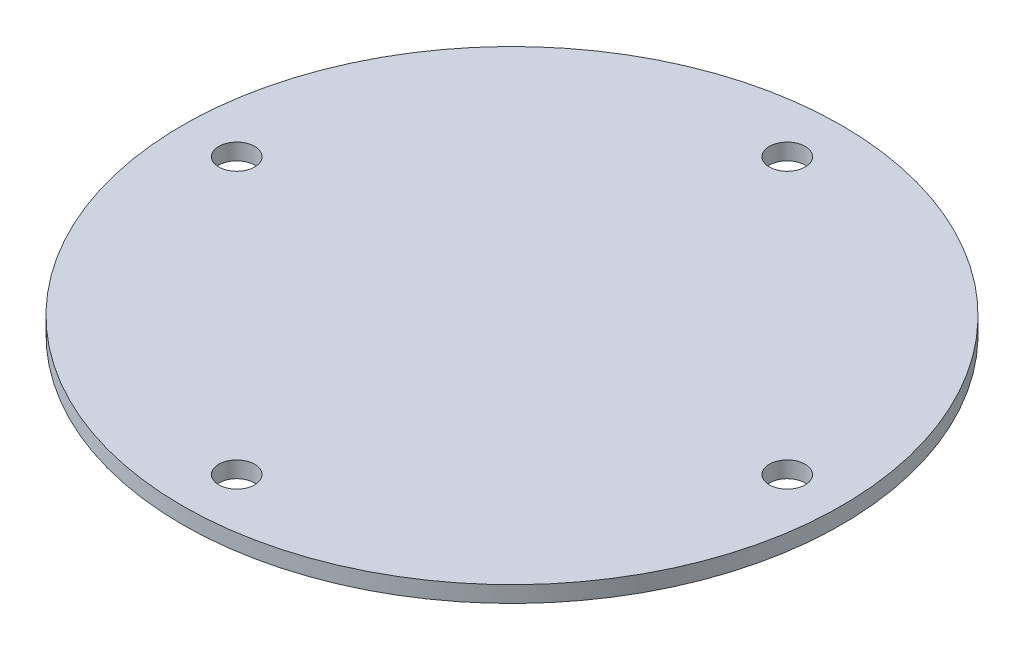
SolidWorks part; units mm, degrees
ref_plane "Front Plane" through (0, 0, 0) normal (0, 0, 1) x (1, 0, 0)
ref_plane "Top Plane" through (0, 0, 0) normal (0, 1, 0) x (1, 0, 0)
ref_plane "Right Plane" through (0, 0, 0) normal (1, 0, 0) x (0, 0, -1)
sketch "Sketch1" plane through (0, 0, 0) normal (0, 1, 0) x (1, 0, 0)
  circle A0 centre (0, 0) radius 60.7
  dimension "Diameter" = 121.4
extrude "Boss-Extrude1" add sketch "Sketch1" along normal mid plane 3
hole_wizard "M6 Clearance Hole1" positions "Sketch8" profile "Sketch9" hole size "M6" standard "ANSI Metric" end condition up to next
sketch "Sketch8" plane through (0, 1.5, 0) normal (0, 1, 0) x (1, 0, 0)
  line L0 (0, 0) -> (50.7, 0) construction
  point P0 (50.7, 0)
  dimension "ThreadedHoleDistance" = 50.7
sketch "Sketch9" plane through (50.7, 1.5, 0) normal (1, 0, 0) x (0, 0, 1)
  line L0 (0, 0) -> (0, 3)
  line L1 (0, 3) -> (3.3, 3)
  line L2 (3.3, 3) -> (3.3, 0)
  line L5 (3.3, 0) -> (0, 0)
  line L11 (0, -6.35) -> (0, 107.95) construction
  dimension "Thru Hole Dia." = 6.6
  dimension "Thru Hole Depth" = 3
pattern_circular "CirPattern2" count 4 over 360 about axis through (0, 0, 0) along (0, 1, 0) of "M6 Clearance Hole1"
sketch "Sketch5" [suppressed] plane through (0, 1.5, 0) normal (0, 1, 0) x (1, 0, 0)
  line L0 (0, 0) -> (65.4, 0) construction
  line L2 (0, 0) -> (39.1737, 39.1737) construction
  circle A0 centre (0, 0) radius 65.4 construction
  dimension "D1" = 45
  dimension " NoseShellHoleRadius" = 0
hole_wizard "M4 Clearance Hole1" [suppressed] positions "Sketch6" profile "Sketch7" hole size "M4" standard "ANSI Metric"
sketch "Sketch6" plane through (0, 1.5, 0) normal (0, 1, 0) x (1, 0, 0)
  point P0 (39.1737, 39.1737)
sketch "Sketch7" plane through (39.1737, 1.5, -39.1737) normal (1, 0, 0) x (0, 0, 1)
  line L0 (0, 0) -> (0, 3)
  line L1 (0, 3) -> (2.15, 3)
  line L2 (2.15, 3) -> (2.15, 0)
  line L5 (2.15, 0) -> (0, 0)
  line L11 (0, -6.35) -> (0, 107.95) construction
  dimension "Thru Hole Dia." = 4.3
  dimension "Thru Hole Depth" = 3
pattern_circular "CirPattern1" [suppressed] count 4 over 360
sketch "Sketch10" [suppressed] plane through (0, 1.5, 0) normal (0, 1, 0) x (1, 0, 0)
  circle A0 centre (0, 0) radius 7.5
  dimension "D1" = 15
extrude "Cut-Extrude1" [suppressed] cut sketch "Sketch10" against normal through all
sketch "Sketch11" [suppressed] plane through (0, -1.5, 0) normal (0, -1, 0) x (1, 0, 0)
  circle A0 centre (-14.75, -5) radius 2.25
  arc A1 (-16.7656, -6) -> (-16.7656, -4) centre (-14.75, -5) ccw construction
  circle A2 centre (-14.75, 5) radius 2.25
  circle A3 centre (34.75, -5) radius 2.25
  circle A4 centre (34.75, 5) radius 2.25
  arc A5 (-16.7656, 4) -> (-16.7656, 6) centre (-14.75, 5) ccw construction
  arc A6 (36.7656, 6) -> (36.7656, 4) centre (34.75, 5) ccw construction
  arc A7 (36.7656, -4) -> (36.7656, -6) centre (34.75, -5) ccw construction
extrude "Cut-Extrude2" [suppressed] cut sketch "Sketch11" against normal through all
sketch "Sketch12" [suppressed] plane through (0, 1.5, 0) normal (0, 1, 0) x (1, 0, 0)
  circle A0 centre (0, 0) radius 65.4 construction
  circle A1 centre (0, 0) radius 65.4
sketch "Sketch13" [suppressed] plane through (0, 1.5, 0) normal (0, 1, 0) x (1, 0, 0)
  line L0 (33.5571, -56.1345) -> (22.4418, -39.5077)
  line L1 (22.4418, -39.5077) -> (27.9287, -35.8397)
  line L2 (27.9287, -35.8397) -> (39.0439, -52.4665)
  line L3 (25.1853, -37.6737) -> (36.3468, -54.3698) construction
  line L4 (25.1853, -37.6737) -> (0, 0) construction
  line L5 (0, 0) -> (0, -55.4) construction
  line L6 (-7.3072, -48.0722) -> (-7.2822, -48.1318)
  line L7 (-7.3072, -48.0722) -> (-7.2822, -48.1318) construction
  line L8 (5.9654, -54.6476) -> (4.6633, -61.2016)
  line L9 (5.9654, -54.6476) -> (4.6633, -61.2016) construction
  line L10 (-13.8383, -61.9557) -> (-10.6131, -45.7223)
  line L11 (-13.8383, -61.9557) -> (-10.6131, -45.7223) construction
  line L12 (-10.6131, -45.7223) -> (-9.717, -41.2115)
  line L13 (-10.6131, -45.7223) -> (-9.717, -41.2115) construction
  line L14 (-9.717, -41.2115) -> (-8.0847, -32.9958)
  line L15 (-9.717, -41.2115) -> (-8.0847, -32.9958) construction
  line L16 (-8.0847, -32.9958) -> (-7.2796, -28.9433)
  line L17 (-8.0847, -32.9958) -> (-7.2796, -28.9433) construction
  line L18 (-7.2796, -28.9433) -> (-2.2975, -3.8666)
  line L19 (-7.2796, -28.9433) -> (-2.2975, -3.8666) construction
  line L20 (-2.2975, -3.8666) -> (0.645, -4.4512)
  line L21 (-2.2975, -3.8666) -> (0.645, -4.4512) construction
  line L22 (0.645, -4.4512) -> (-4.3371, -29.5279)
  line L23 (0.645, -4.4512) -> (-4.3371, -29.5279) construction
  line L24 (-4.3371, -29.5279) -> (-5.1422, -33.5804)
  line L25 (-4.3371, -29.5279) -> (-5.1422, -33.5804) construction
  line L26 (-5.1422, -33.5804) -> (-6.7745, -41.7961)
  line L27 (-5.1422, -33.5804) -> (-6.7745, -41.7961) construction
  line L28 (-6.7745, -41.7961) -> (-7.6706, -46.3069)
  line L29 (-6.7745, -41.7961) -> (-7.6706, -46.3069) construction
  circle A0 centre (0, 0) radius 65.4 construction
  circle A1 centre (0, 0) radius 65.4
  arc A2 (33.5571, -56.1345) -> (39.0439, -52.4665) centre (0, 0) ccw
  arc A3 (-7.2822, -48.1318) -> (0.9663, -48.6742) centre (0.0376, 0.1893) ccw
  arc A4 (-7.2822, -48.1318) -> (0.9663, -48.6742) centre (0.0376, 0.1893) ccw construction
  arc A5 (5.9654, -54.6476) -> (0.9663, -48.6742) centre (1.0613, -53.6733) ccw
  arc A6 (5.9654, -54.6476) -> (0.9663, -48.6742) centre (1.0613, -53.6733) ccw construction
  arc A7 (-0.2638, -65.2272) -> (4.6633, -61.2016) centre (-0.2408, -60.2272) ccw
  arc A8 (-0.2638, -65.2272) -> (4.6633, -61.2016) centre (-0.2408, -60.2272) ccw construction
  arc A9 (-10.5087, -64.3722) -> (-0.2638, -65.2272) centre (0.0376, 0.1893) ccw
  arc A10 (-10.5087, -64.3722) -> (-0.2638, -65.2272) centre (0.0376, 0.1893) ccw construction
  spline S0 degree 3 poles (-851.9646, -2942.8185) (60.4248, -65.7152) (17.8504, -79.9431) (-12.3758, -63.3729) (-13.1243, -62.9075) (-13.5648, -62.5349) (-13.7339, -62.3268) (-13.8027, -62.2127) (-15.1865, -57.8662) (54.9429, -40.9019) (-2900.9164, -875.9568) knots -23.643273 -23.643273 -23.643273 -23.643273 0.25 0.5 0.75 0.875 0.90625 0.9375 0.96875 4.171829 4.171829 4.171829 4.171829 only from (-10.5087, -64.3722) to (-13.8383, -61.9557)
  spline S1 degree 3 poles (-10.5087, -64.3722) (-10.8215, -64.2088) (-11.4465, -63.8823) (-12.3758, -63.3729) (-13.1243, -62.9075) (-13.5648, -62.5349) (-13.7339, -62.3268) (-13.8027, -62.2127) (-13.8424, -62.0879) (-13.8422, -62) (-13.8383, -61.9557) knots 0 0 0 0 0.25 0.5 0.75 0.875 0.90625 0.9375 0.96875 1 1 1 1 construction
  spline S2 degree 3 poles (-3007.5234, -22.9557) (34.2167, -32.9245) (-7.4634, -39.6228) (-7.7013, -46.6474) (-7.6977, -46.7608) (-7.6875, -46.8738) (-7.6712, -46.9863) (-7.6495, -47.098) (-7.5964, -47.3201) (-3.3838, -59.7446) (38.0106, -60.1077) (-2841.7572, -1030.2239) knots -11.347292 -11.347292 -11.347292 -11.347292 0.125 0.1875 0.25 0.3125 0.375 0.4375 0.5 0.75 21.8368 21.8368 21.8368 21.8368 only from (-7.6706, -46.3069) to (-7.3072, -48.0722)
  spline S3 degree 3 poles (-7.6706, -46.3069) (-7.6813, -46.3825) (-7.6961, -46.496) (-7.7013, -46.6474) (-7.6977, -46.7608) (-7.6875, -46.8738) (-7.6712, -46.9863) (-7.6495, -47.098) (-7.5964, -47.3201) (-7.4857, -47.6466) (-7.3668, -47.9303) (-7.3072, -48.0722) knots 0 0 0 0 0.125 0.1875 0.25 0.3125 0.375 0.4375 0.5 0.75 1 1 1 1 construction
  dimension "D2" = 6.6
  dimension "D3" = 25
  dimension "D4" = 45
  dimension "D1" = 0
extrude "Cut-Extrude3" [suppressed] cut sketch "Sketch13" against normal through all
pattern_circular "CirPattern3" [suppressed] count 4 over 360
